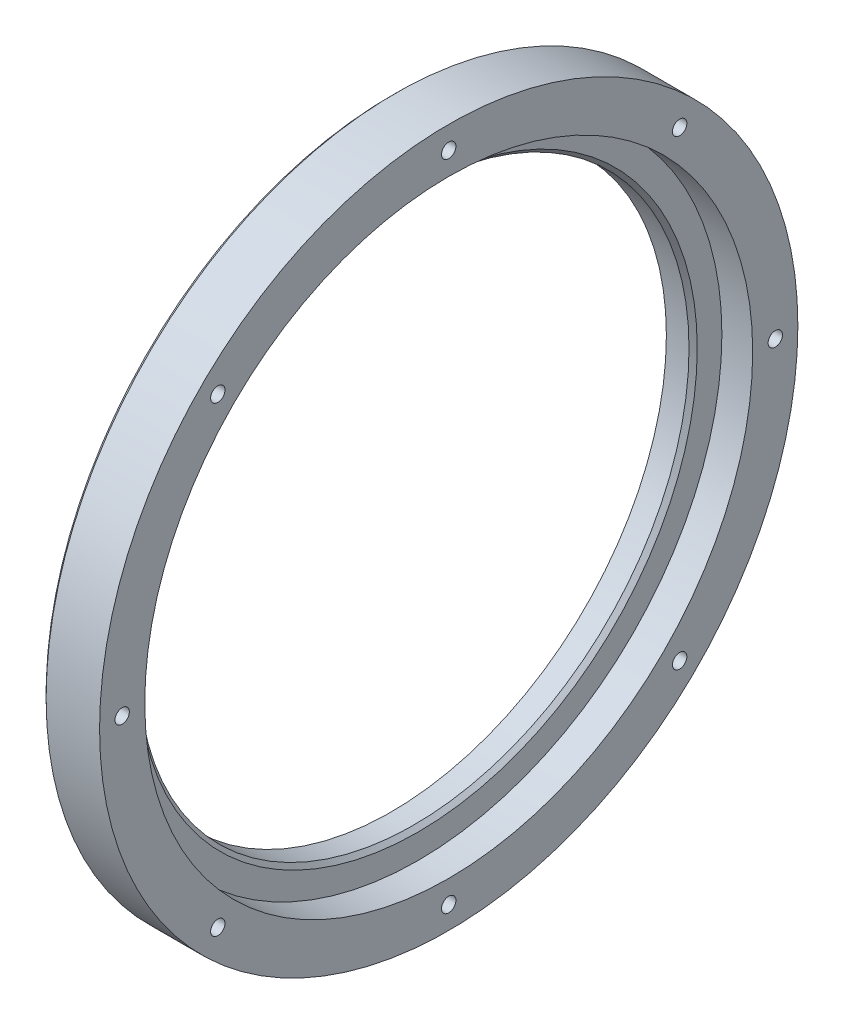
SolidWorks part; units mm, degrees
ref_plane "Płaszczyzna przednia" through (0, 0, 0) normal (0, 0, 1) x (1, 0, 0)
ref_plane "Płaszczyzna górna" through (0, 0, 0) normal (0, 1, 0) x (1, 0, 0)
ref_plane "Płaszczyzna prawa" through (0, 0, 0) normal (1, 0, 0) x (0, 0, -1)
sketch "Szkic1" plane through (0, 0, 0) normal (0, 0, 1) x (1, 0, 0)
  line L0 (-272.858, 75.0093) -> (-280.358, 75.0093)
  line L1 (-272.858, -79.75) -> (-272.858, 79.75) construction
  line L2 (-272.858, 86.0093) -> (-272.858, -83.9907) construction
  line L3 (-280.358, 75.0093) -> (-280.358, 68.0093)
  line L4 (-280.358, 68.0093) -> (-286.8712, 68.0093)
  line L5 (-286.8712, 68.0093) -> (-286.8712, 85.0093)
  line L6 (-285.8712, 86.0093) -> (-272.858, 86.0093)
  line L7 (-252.858, 86.0093) -> (-272.858, 86.0093) construction
  line L8 (-268.908, 1.0093) -> (-389.244, 1.0093) construction
  line L10 (-286.8712, 85.0093) -> (-285.8712, 86.0093)
  line L11 (-279.858, -79.2) -> (-279.858, 79.2) construction
  line L12 (-272.858, 75.0093) -> (-272.858, 86.0093)
  line L13 (-268.908, -49.9907) -> (-268.908, 52.0093) construction
  point P4 (-286.8712, 86.0093)
  dimension "D1" = 1.5
  dimension "D2" = 18
  dimension "D3" = 0.5
revolve "Obrót1" add sketch "Szkic1" angle 360 about L8
sketch "Szkic2" plane through (-286.8712, 0, 0) normal (-1, 0, 0) x (0, 0, 1)
  line L0 (0, 1.0093) -> (67, 1.0093) construction
  line L1 (74, 1.0093) -> (85, 1.0093) construction
  line L2 (0, 1.0093) -> (47.3762, -46.3669) construction
  line L3 (52.3259, -51.3166) -> (60.1041, -59.0948) construction
  line L4 (0, 1.0093) -> (0, -65.9907) construction
  line L5 (0, -72.9907) -> (0, -83.9907) construction
  line L6 (0, 1.0093) -> (-47.3762, -46.3669) construction
  line L7 (-52.3259, -51.3166) -> (-60.1041, -59.0948) construction
  line L8 (0, 1.0093) -> (-67, 1.0093) construction
  line L9 (-74, 1.0093) -> (-85, 1.0093) construction
  line L10 (0, 1.0093) -> (-47.3762, 48.3854) construction
  line L11 (-52.3259, 53.3352) -> (-60.1041, 61.1133) construction
  line L12 (0, 1.0093) -> (0, 68.0093) construction
  line L13 (0, 75.0093) -> (0, 86.0093) construction
  line L14 (0, 1.0093) -> (47.3762, 48.3854) construction
  line L15 (52.3259, 53.3352) -> (60.1041, 61.1133) construction
  circle A0 centre (0, 1.0093) radius 85 construction
  circle A1 centre (79.5, 1.0093) radius 1.75
  circle A2 centre (59.9476, 1.0093) radius 1.75 construction
  circle A3 centre (0, 1.0093) radius 74 construction
  circle A4 centre (0, 1.0093) radius 67 construction
  circle A5 centre (56.215, -55.2057) radius 1.75
  circle A6 centre (0, -78.4907) radius 1.75
  circle A7 centre (-56.215, -55.2057) radius 1.75
  circle A8 centre (-79.5, 1.0093) radius 1.75
  circle A9 centre (-56.215, 57.2243) radius 1.75
  circle A10 centre (0, 80.5093) radius 1.75
  circle A11 centre (56.215, 57.2243) radius 1.75
  point P58 (0, 1.0093)
extrude "Wytnij-wyciągnięcie1" cut sketch "Szkic2" against normal through all
sketch "Szkic4" plane through (-286.8712, 0, 0) normal (-1, 0, 0) x (0, 0, 1)
  line L0 (0, 1.0093) -> (91.9385, 1.0093) construction
  line L1 (0, 1.0093) -> (65.0103, -64.0011) construction
  line L2 (0, 1.0093) -> (0, -90.9292) construction
  line L3 (0, 1.0093) -> (-65.0103, -64.0011) construction
  line L4 (0, 1.0093) -> (-91.9385, 1.0093) construction
  line L5 (0, 1.0093) -> (-65.0103, 66.0196) construction
  line L6 (0, 1.0093) -> (0, 92.9478) construction
  line L7 (0, 1.0093) -> (65.0103, 66.0196) construction
  circle A0 centre (79.5, 1.0093) radius 3
  circle A1 centre (59.9476, 1.0093) radius 3 construction
  circle A2 centre (56.215, -55.2057) radius 3
  circle A3 centre (0, -78.4907) radius 3
  circle A4 centre (-56.215, -55.2057) radius 3
  circle A5 centre (-79.5, 1.0093) radius 3
  circle A6 centre (-56.215, 57.2243) radius 3
  circle A7 centre (0, 80.5093) radius 3
  circle A8 centre (56.215, 57.2243) radius 3
  point P32 (0, 1.0093)
extrude "Wytnij-wyciągnięcie2" cut sketch "Szkic4" against normal blind 4
chamfer "Sfazowanie1" distance 1 angle 45 1 edges at (-280.358, 1.0093, -67)
move or copy body "Obiekt-Przenieś/Kopiuj1" [suppressed] bodies to move or copy 103 copy no rotation origin (-139.9323, 1.0093, 139.9323) rotation axis (0.7071, 0, 0.7071) rotation angle 180
